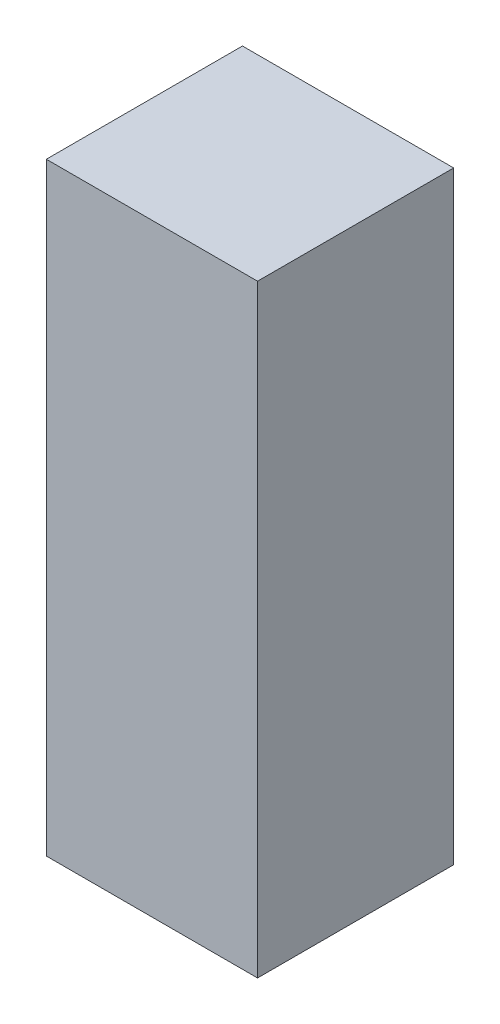
SolidWorks part; units mm, degrees
ref_plane "Front Plane" through (0, 0, 0) normal (0, 0, 1) x (1, 0, 0)
ref_plane "Top Plane" through (0, 0, 0) normal (0, 1, 0) x (1, 0, 0)
ref_plane "Right Plane" through (0, 0, 0) normal (1, 0, 0) x (0, 0, -1)
other "Configuration Table"
sketch "Sketch1" plane through (0, 0, 0) normal (0, 0, 1) x (1, 0, 0)
  line L1 (24, 1870) -> (38, 1870)
  line L2 (24, 1870) -> (24, 1910)
  line L3 (24, 1910) -> (38, 1910)
  line L4 (38, 1870) -> (38, 1910)
extrude "OVEN_fan_filtre_kapagi_mentese_2_1" add sketch "Sketch1" along normal blind 13 from offset 20 separate body
